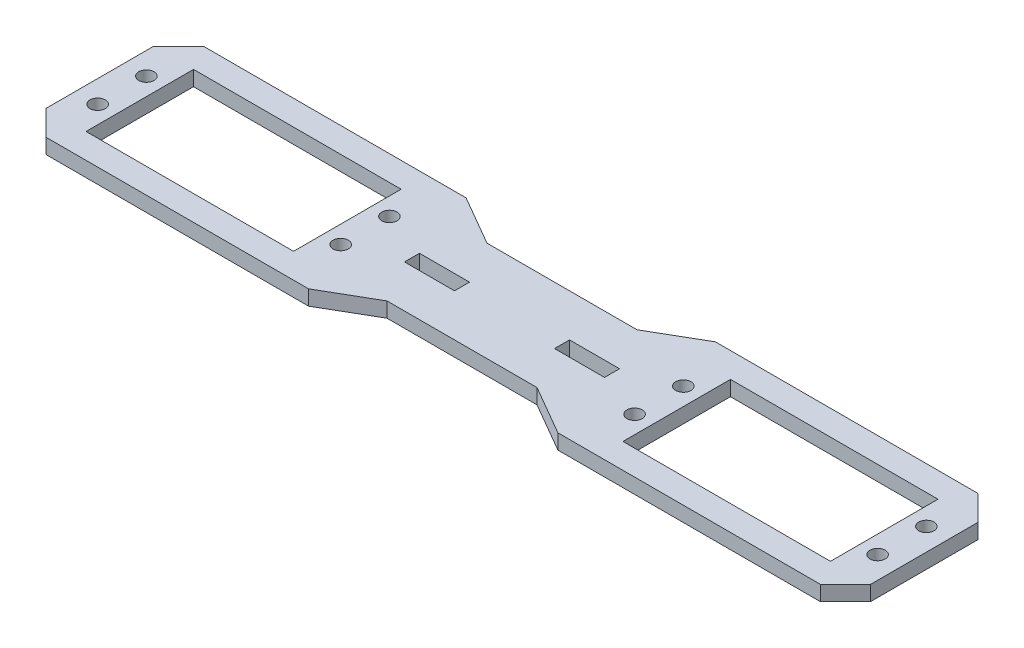
SolidWorks part; units mm, degrees
ref_plane "前视基准面" through (0, 0, 0) normal (0, 0, 1) x (1, 0, 0)
ref_plane "上视基准面" through (0, 0, 0) normal (0, 1, 0) x (1, 0, 0)
ref_plane "右视基准面" through (0, 0, 0) normal (1, 0, 0) x (0, 0, -1)
sketch "草图1" plane through (0, 0, 0) normal (0, 1, 0) x (1, 0, 0)
  line L0 (-92.2198, 0) -> (92.2198, 0) construction
  line L1 (0, 54.1749) -> (0, -54.1749) construction
  line L2 (15, 10) -> (-15, 10)
  line L3 (-15, 10) -> (-24.93, 15.75)
  line L4 (-24.93, 15.75) -> (-77.43, 15.75)
  line L5 (-77.43, 15.75) -> (-82.43, 10.75)
  line L6 (-82.43, 10.75) -> (-82.43, -10.75)
  line L7 (-74.43, -10.75) -> (-74.43, 10.75)
  line L8 (-74.43, 10.75) -> (-32.93, 10.75)
  line L9 (-32.93, 10.75) -> (-32.93, -10.75)
  line L10 (-20, -1.5) -> (-20, 1.5)
  line L11 (-20, 1.5) -> (-10, 1.5)
  line L12 (-10, 1.5) -> (-10, -1.5)
  line L13 (-20, -1.5) -> (-10, -1.5)
  line L14 (-74.43, -10.75) -> (-32.93, -10.75)
  line L15 (-77.43, -15.75) -> (-82.43, -10.75)
  line L16 (-24.93, -15.75) -> (-77.43, -15.75)
  line L17 (-15, -10) -> (-24.93, -15.75)
  line L18 (15, -10) -> (-15, -10)
  line L19 (15, -10) -> (24.93, -15.75)
  line L20 (24.93, -15.75) -> (77.43, -15.75)
  line L21 (77.43, -15.75) -> (82.43, -10.75)
  line L22 (74.43, -10.75) -> (32.93, -10.75)
  line L23 (20, -1.5) -> (10, -1.5)
  line L24 (10, 1.5) -> (10, -1.5)
  line L25 (20, 1.5) -> (10, 1.5)
  line L26 (20, -1.5) -> (20, 1.5)
  line L27 (32.93, 10.75) -> (32.93, -10.75)
  line L28 (74.43, 10.75) -> (32.93, 10.75)
  line L29 (74.43, -10.75) -> (74.43, 10.75)
  line L30 (82.43, 10.75) -> (82.43, -10.75)
  line L31 (77.43, 15.75) -> (82.43, 10.75)
  line L32 (24.93, 15.75) -> (77.43, 15.75)
  line L33 (15, 10) -> (24.93, 15.75)
  circle A0 centre (-77.98, 4.875) radius 1.525
  circle A1 centre (-77.98, -4.875) radius 1.525
  circle A2 centre (77.98, -4.875) radius 1.525
  circle A3 centre (77.98, 4.875) radius 1.525
  circle A4 centre (-29.38, 4.875) radius 1.525
  circle A5 centre (-29.38, -4.875) radius 1.525
  circle A6 centre (29.38, -4.875) radius 1.525
  circle A7 centre (29.38, 4.875) radius 1.525
  point P0 (82.43, 0)
  point P4 (0, 0)
  point P8 (0, 0)
  point P15 (-53.68, 10.75)
  point P27 (-10, 0)
  point P28 (-20, 0)
  point P29 (-32.93, 0)
  point P30 (-74.43, 0)
  point P31 (-82.43, 0)
  point P40 (0, -10)
  point P55 (0, 10)
  point P56 (74.43, 0)
  point P57 (32.93, 0)
  point P58 (20, 0)
  point P59 (10, 0)
  point P64 (-35.8345, 9.6156)
  point P65 (-29.744, 0)
  dimension "D16" = 3.05
  dimension "D17" = 3.05
  dimension "D1" = 31.5
  dimension "D2" = 164.86
  dimension "D3" = 15
  dimension "D4" = 57.5
  dimension "D5" = 5.75
  dimension "D6" = 5
  dimension "D7" = 5
  dimension "D8" = 8
  dimension "D9" = 41.5
  dimension "D10" = 4.45
  dimension "D11" = 45
  dimension "D12" = 9.75
  dimension "D13" = 10
  dimension "D14" = 1.5
  dimension "D15" = 10
  dimension "D18" = 48.6
  dimension "D19" = 9.75
extrude "凸台-拉伸1" add sketch "草图1" along normal blind 3
